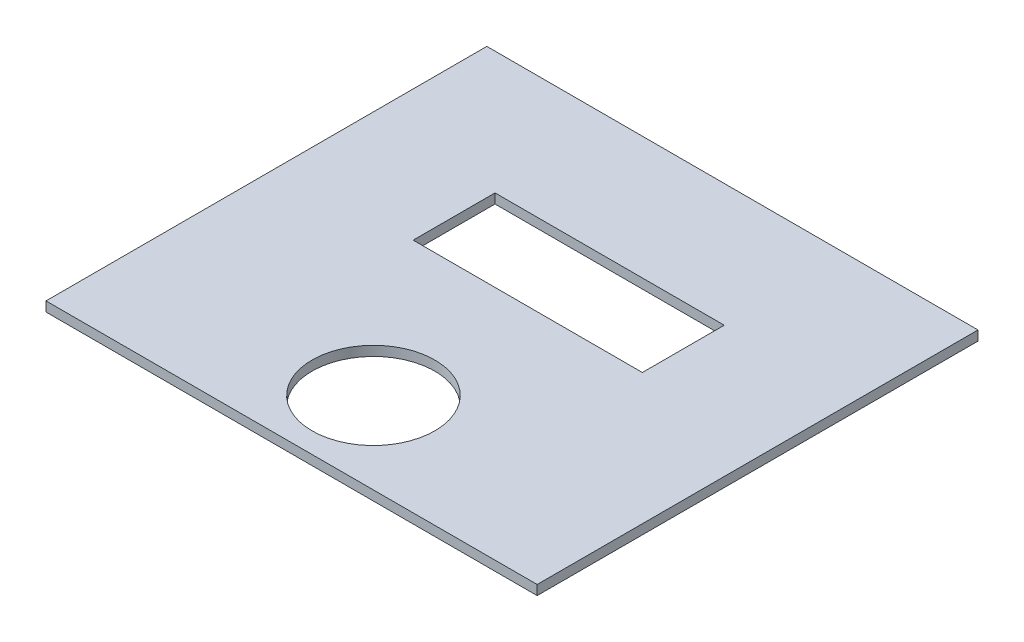
SolidWorks part; units mm, degrees
material "Oak"
ref_plane "Front Plane" through (0, 0, 0) normal (0, 0, 1) x (1, 0, 0)
ref_plane "Top Plane" through (0, 0, 0) normal (0, 1, 0) x (1, 0, 0)
ref_plane "Right Plane" through (0, 0, 0) normal (1, 0, 0) x (0, 0, -1)
sketch "Sketch1" plane through (0, 0, 0) normal (0, 1, 0) x (1, 0, 0)
  line L0 (0, 68.392) -> (0, 17.592) construction
  line L1 (-76.2, 68.392) -> (76.2, 68.392)
  line L2 (-76.2, 68.392) -> (-76.2, -68.392)
  line L3 (-76.2, -68.392) -> (76.2, -68.392)
  line L4 (76.2, 68.392) -> (76.2, -68.392)
  line L5 (-76.2, 68.392) -> (76.2, -68.392) construction
  line L6 (-76.2, -68.392) -> (76.2, 68.392) construction
  line L7 (0, -68.392) -> (0, -42.992) construction
  line L8 (-35.56, 4.892) -> (35.56, 4.892)
  line L9 (-35.56, 4.892) -> (-35.56, 30.292)
  line L10 (-35.56, 30.292) -> (35.56, 30.292)
  line L11 (35.56, 4.892) -> (35.56, 30.292)
  line L12 (-35.56, 4.892) -> (35.56, 30.292) construction
  line L13 (-35.56, 30.292) -> (35.56, 4.892) construction
  circle A0 centre (0, -42.992) radius 19.05
  point P0 (0, 0)
  dimension "D7" = 38.1
  dimension "D1" = 136.7841
  dimension "D2" = 152.4
  dimension "D3" = 50.8
  dimension "D4" = 71.12
  dimension "D5" = 25.4
  dimension "D6" = 25.4
extrude "Boss-Extrude1" add sketch "Sketch1" along normal blind 3
